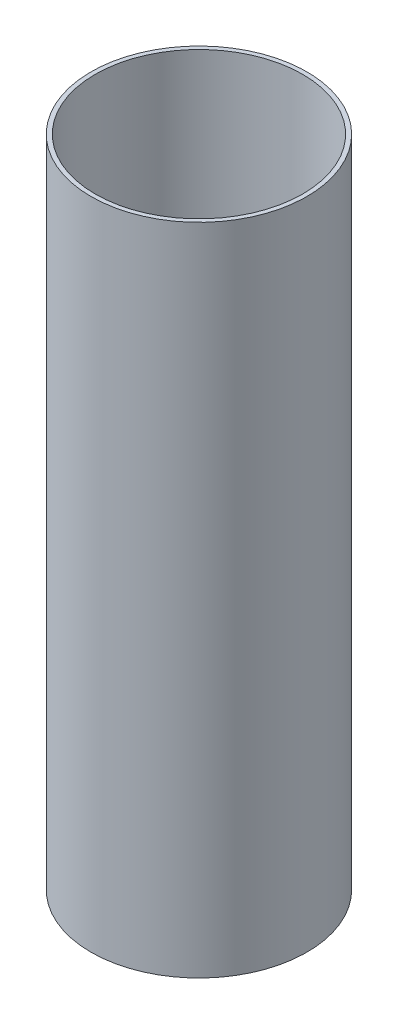
SolidWorks part; units mm, degrees
ref_plane "Front Plane" through (0, 0, 0) normal (0, 0, 1) x (1, 0, 0)
ref_plane "Top Plane" through (0, 0, 0) normal (0, 1, 0) x (1, 0, 0)
ref_plane "Right Plane" through (0, 0, 0) normal (1, 0, 0) x (0, 0, -1)
sketch "Sketch1" plane through (0, 0, 0) normal (0, 1, 0) x (1, 0, 0)
  circle A0 centre (0, 0) radius 37.95
  circle A1 centre (0, 0) radius 36.45
  dimension "D1" = 75.9
  dimension "D2" = 72.9
extrude "Boss-Extrude1" add sketch "Sketch1" along normal blind 230
